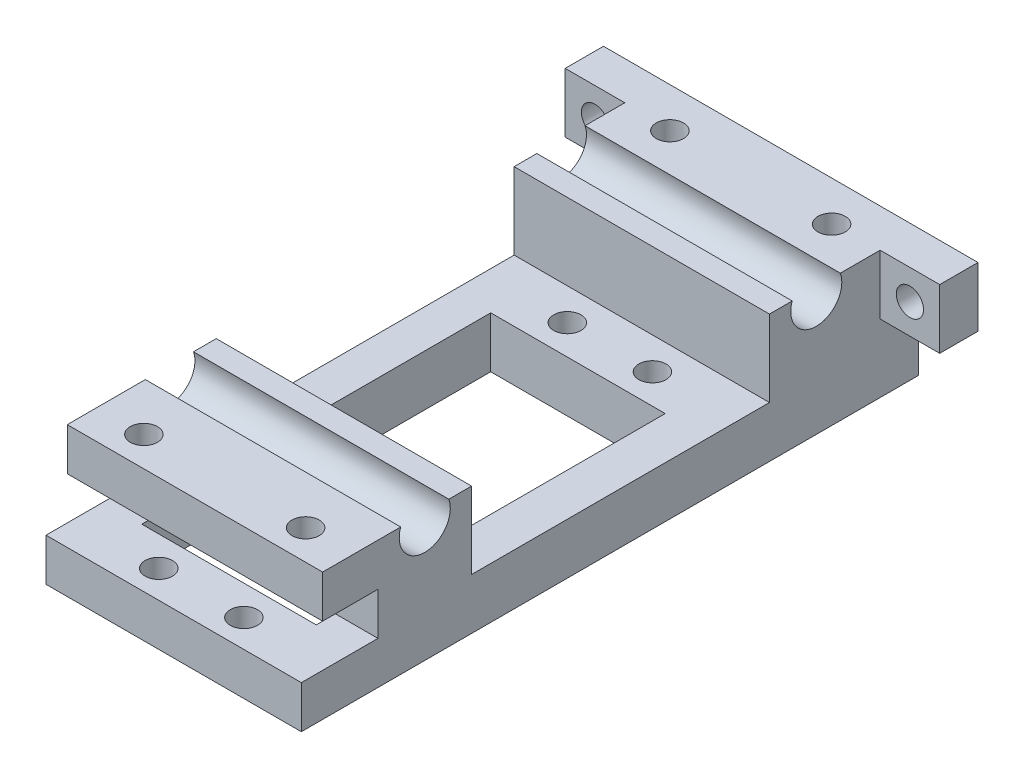
SolidWorks part; units mm, degrees
material "PLA+"
ref_plane "Front Plane" through (0, 0, 0) normal (0, 0, 1) x (1, 0, 0)
ref_plane "Top Plane" through (0, 0, 0) normal (0, 1, 0) x (1, 0, 0)
ref_plane "Right Plane" through (0, 0, 0) normal (1, 0, 0) x (0, 0, -1)
sketch "Sketch1" plane through (0, 0, 0) normal (0, 1, 0) x (1, 0, 0)
  line L1 (-15, -36.25) -> (15, -36.25)
  line L2 (-15, -36.25) -> (-15, 36.25)
  line L3 (-15, 36.25) -> (15, 36.25)
  line L4 (15, -36.25) -> (15, 36.25)
  line L5 (-15, -36.25) -> (15, 36.25) construction
  line L6 (-15, 36.25) -> (15, -36.25) construction
  point P0 (0, 0)
  dimension "D1" = 72.5
  dimension "D2" = 30
extrude "Boss-Extrude1" add sketch "Sketch1" along normal blind 15
sketch "Sketch2" plane through (0, 0, 0) normal (0, -1, 0) x (1, 0, 0)
  line L0 (-15, 36.25) -> (15, 36.25) construction
  line L1 (-10.5, 29.5) -> (10, 29.5)
  line L2 (-10.5, 29.5) -> (-10.5, -11.5)
  line L3 (-10.5, -11.5) -> (10, -11.5)
  line L4 (10, 29.5) -> (10, -11.5)
  line L5 (-10.5, 29.5) -> (10, -11.5) construction
  line L6 (-10.5, -11.5) -> (10, 29.5) construction
  line L7 (15, 36.25) -> (15, -36.25) construction
  point P0 (-0.25, 9)
  dimension "D1" = 6.75
  dimension "D2" = 5
  dimension "D3" = 41
  dimension "D4" = 20.5
extrude "Cut-Extrude1" cut sketch "Sketch2" against normal blind 8 contours L4 L3 L2 L1
sketch "Sketch3" plane through (0, 15, 0) normal (0, 1, 0) x (1, 0, 0)
  line L0 (-15, 36.25) -> (-15, -36.25) construction
  line L1 (-15, -16.25) -> (15, -16.25)
  line L2 (-15, -16.25) -> (-15, 18.75)
  line L3 (-15, 18.75) -> (15, 18.75)
  line L4 (15, -16.25) -> (15, 18.75)
  line L5 (15, -36.25) -> (15, 36.25) construction
  line L6 (-15, -36.25) -> (15, -36.25) construction
  dimension "D1" = 35
  dimension "D2" = 20
extrude "Cut-Extrude2" cut sketch "Sketch3" against normal blind 9
sketch "Sketch4" plane through (15, 0, 0) normal (1, 0, 0) x (0, 0, -1)
  line L0 (-33.75, 15) -> (-33.75, 10)
  line L1 (-36.25, 15) -> (-16.25, 15) construction
  line L2 (-33.75, 10) -> (-27.25, 10)
  line L3 (-27.25, 10) -> (-27.25, 5)
  line L4 (-27.25, 5) -> (-36.25, 5)
  line L5 (-36.25, 15) -> (-36.25, 0) construction
  line L6 (-36.25, 5) -> (-36.25, 15)
  line L7 (-36.25, 15) -> (-33.75, 15)
  line L8 (-36.25, 0) -> (36.25, 0) construction
  dimension "D1" = 2.5
  dimension "D2" = 9
  dimension "D3" = 5
  dimension "D4" = 5
extrude "Cut-Extrude3" cut sketch "Sketch4" against normal through all
sketch "Sketch5" plane through (0, 0, 0) normal (0, -1, 0) x (1, 0, 0)
  line L0 (-10.5, -11.5) -> (10, -11.5) construction
  line L2 (-10.5, 29.5) -> (10, 29.5) construction
  circle A0 centre (-5, 33) radius 1.6
  circle A1 centre (5, 33) radius 1.6
  circle A2 centre (-5, -15) radius 1.6
  circle A3 centre (5, -15) radius 1.6
  dimension "D1" = 3.2
  dimension "D2" = 3.2
  dimension "D3" = 3.2
  dimension "D4" = 3.2
  dimension "D5" = 10
  dimension "D6" = 5
  dimension "D7" = 3.5
  dimension "D8" = 3.5
extrude "Cut-Extrude4" cut sketch "Sketch5" against normal up to next
sketch "Sketch6" plane through (15, 0, 0) normal (1, 0, 0) x (0, 0, -1)
  line L0 (18.75, 15) -> (36.25, 15) construction
  line L1 (36.25, 15) -> (36.25, 0) construction
  circle A0 centre (24.25, 14) radius 3
  circle A1 centre (-21.75, 14) radius 3
  dimension "D2" = 6
  dimension "D3" = 6
  dimension "D1" = 1
  dimension "D4" = 12
  dimension "D5" = 46
extrude "Cut-Extrude5" cut sketch "Sketch6" against normal through all
sketch "Sketch7" plane through (0, 15, 0) normal (0, 1, 0) x (1, 0, 0)
  line L0 (15, -33.75) -> (15, -24.5784) construction
  line L1 (-15, -24.5784) -> (-15, -33.75) construction
  line L2 (-15, -33.75) -> (15, -33.75) construction
  line L3 (15, 36.25) -> (-15, 36.25) construction
  circle A0 centre (-9.5, -30.25) radius 1.6
  circle A1 centre (9.5, -30.25) radius 1.6
  circle A2 centre (-9.5, 31.55) radius 1.6
  circle A3 centre (9.5, 31.55) radius 1.6
  dimension "D1" = 3.2
  dimension "D2" = 3.2
  dimension "D3" = 5.5
  dimension "D6" = 3.2
  dimension "D7" = 3.2
  dimension "D4" = 5.5
  dimension "D5" = 3.5
  dimension "D8" = 4.7
extrude "Cut-Extrude6" cut sketch "Sketch7" against normal up to next
sketch "Sketch8" plane through (0, 0, -36.25) normal (0, 0, -1) x (-1, 0, 0)
  line L1 (15, 15) -> (22, 15)
  line L2 (15, 15) -> (15, 8)
  line L3 (15, 8) -> (22, 8)
  line L4 (22, 15) -> (22, 8)
  line L5 (-15, 15) -> (-22, 15)
  line L6 (-15, 15) -> (-15, 8)
  line L7 (-15, 8) -> (-22, 8)
  line L8 (-22, 15) -> (-22, 8)
  dimension "D1" = 7
  dimension "D2" = 7
  dimension "D3" = 7
  dimension "D4" = 7
extrude "Boss-Extrude2" add sketch "Sketch8" against normal blind 4.5
sketch "Sketch9" plane through (0, 0, -36.25) normal (0, 0, -1) x (-1, 0, 0)
  line L0 (-22, 15) -> (22, 15) construction
  line L1 (22, 8) -> (22, 15) construction
  line L2 (-22, 15) -> (-22, 8) construction
  line L3 (-22, 8) -> (-15, 8) construction
  circle A0 centre (18.5, 11.5) radius 1.6
  circle A1 centre (-18.5, 11.5) radius 1.6
  dimension "D1" = 3.2
  dimension "D2" = 3.2
  dimension "D3" = 3.5
  dimension "D4" = 3.5
  dimension "D5" = 3.5
  dimension "D6" = 3.5
extrude "Cut-Extrude7" cut sketch "Sketch9" against normal up to next
